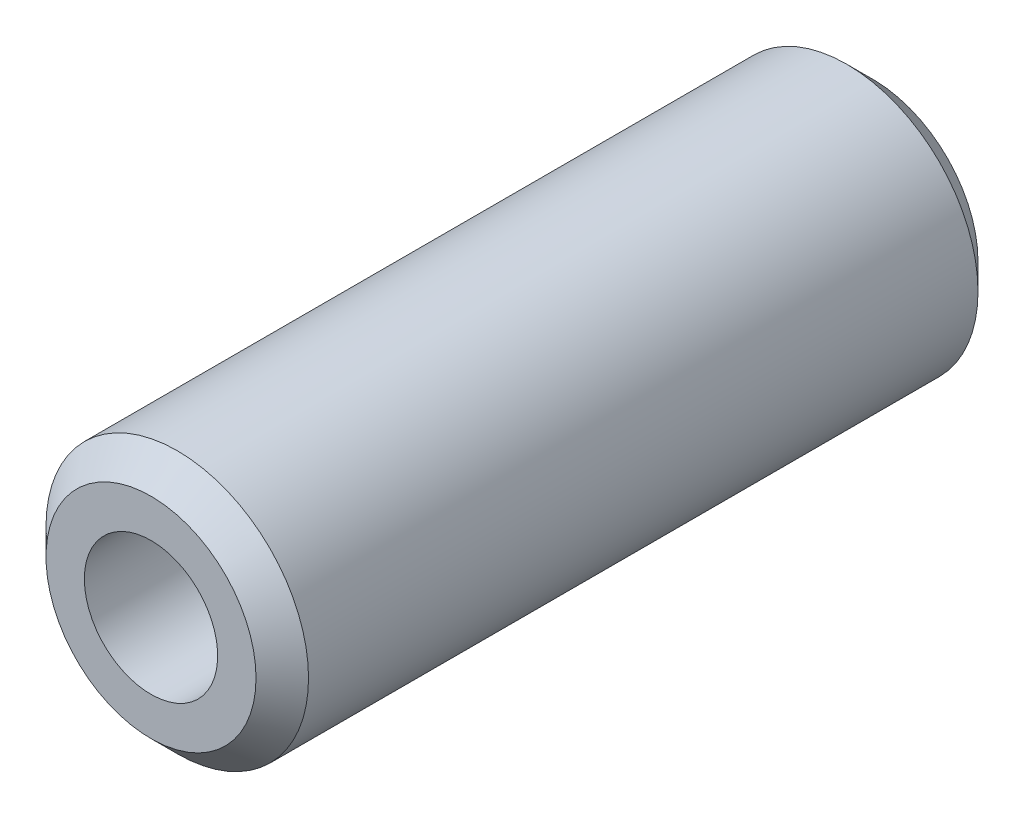
SolidWorks part; units mm, degrees
ref_plane "Front Plane" through (0, 0, 0) normal (0, 0, 1) x (1, 0, 0)
ref_plane "Top Plane" through (0, 0, 0) normal (0, 1, 0) x (1, 0, 0)
ref_plane "Right Plane" through (0, 0, 0) normal (1, 0, 0) x (0, 0, -1)
sketch "Sketch1" plane through (0, 0, 0) normal (0, 0, 1) x (1, 0, 0)
  circle A0 centre (0, 0) radius 12.7
  dimension "D1" = 25.4
extrude "Boss-Extrude1" add sketch "Sketch1" along normal blind 69.85
sketch "Sketch2" plane through (0, 0, 0) normal (0, 0, -1) x (-1, 0, 0)
  circle A0 centre (0, 0) radius 6.45
  dimension "D1" = 12.9
extrude "Cut-Extrude1" cut sketch "Sketch2" against normal through all
chamfer "Chamfer1" distance 2.54 angle 45 2 edges at (12.7, 0, 69.85) (12.7, 0, 0)
